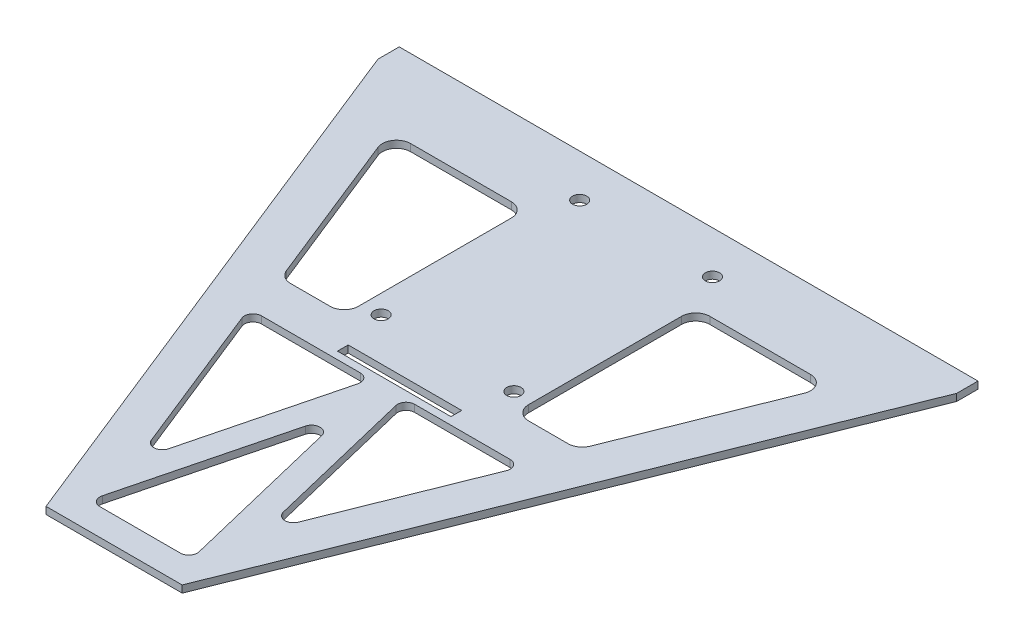
SolidWorks part; units mm, degrees
material "Teak"
ref_plane "Front Plane" through (0, 0, 0) normal (0, 0, 1) x (1, 0, 0)
ref_plane "Top Plane" through (0, 0, 0) normal (0, 1, 0) x (1, 0, 0)
ref_plane "Right Plane" through (0, 0, 0) normal (1, 0, 0) x (0, 0, -1)
sketch "Sketch2" plane through (0, 0, 0) normal (0, 1, 0) x (1, 0, 0)
  line L0 (0, 0) -> (259.08, 0)
  line L1 (259.08, 0) -> (160.02, -247.65)
  line L2 (160.02, -247.65) -> (99.06, -247.65)
  line L3 (99.06, -247.65) -> (0, 0)
  line L4 (0, 0) -> (0, -247.65) construction
  line L5 (0, -247.65) -> (400.3627, -247.65) construction
  line L6 (152.0793, -235.7108) -> (106.3593, -235.7108)
  line L7 (106.3593, -235.7108) -> (129.7724, -143.639)
  line L8 (129.7724, -143.639) -> (152.0793, -235.7108)
  line L9 (101.2964, -209.2418) -> (122.5734, -125.57)
  line L10 (122.5734, -125.57) -> (67.8277, -125.57)
  line L11 (67.8277, -125.57) -> (101.2964, -209.2418)
  line L12 (157.2265, -208.4139) -> (190.3641, -125.57)
  line L13 (190.3641, -125.57) -> (137.1554, -125.57)
  line L14 (137.1554, -125.57) -> (157.2265, -208.4139)
  dimension "D1" = 259.08
  dimension "D2" = 60.96
  dimension "D3" = 247.65
  dimension "D6" = 45.72
  dimension "D7" = 11.43
  dimension "D8" = 11.43
extrude "Boss-Extrude1" add sketch "Sketch2" along normal blind 3.175
fillet "Fillet1" radius 3.81 9 edges at (106.3593, 1.5875, 235.7108) (101.2964, 1.5875, 209.2418) (157.2265, 1.5875, 208.4139) (152.0793, 1.5875, 235.7108) (129.7724, 1.5875, 143.639) (122.5734, 1.5875, 125.57) (67.8277, 1.5875, 125.57) (137.1554, 1.5875, 125.57) (190.3641, 1.5875, 125.57)
sketch "Sketch3" plane through (0, 3.175, 0) normal (0, 1, 0) x (1, 0, 0)
  line L0 (129.54, 0) -> (129.54, -306.5161) construction
  line L1 (259.08, 0) -> (0, 0) construction
  line L2 (167.64, -25.4) -> (228.4025, -25.4)
  line L3 (228.4025, -25.4) -> (195.9545, -106.52)
  line L4 (195.9545, -106.52) -> (167.64, -106.52)
  line L5 (167.64, -106.52) -> (167.64, -25.4)
  line L6 (160.02, -247.65) -> (259.08, 0) construction
  line L7 (184.7366, -125.57) -> (141.9987, -125.57) construction
  line L8 (91.44, -106.52) -> (91.44, -25.4)
  line L9 (63.1255, -106.52) -> (91.44, -106.52)
  line L10 (30.6775, -25.4) -> (63.1255, -106.52)
  line L11 (91.44, -25.4) -> (30.6775, -25.4)
  dimension "D1" = 25.4
  dimension "D2" = 19.05
  dimension "D3" = 19.05
  dimension "D4" = 38.1
extrude "Cut-Extrude1" cut sketch "Sketch3" against normal up to surface (3.175 mm away) up to face at (129.54, 0, 123.825)
fillet "Fillet2" radius 6.35 8 edges at (167.64, 1.5875, 106.52) (195.9545, 1.5875, 106.52) (91.44, 1.5875, 106.52) (63.1255, 1.5875, 106.52) (91.44, 1.5875, 25.4) (30.6775, 1.5875, 25.4) (167.64, 1.5875, 25.4) (228.4025, 1.5875, 25.4)
sketch "Sketch4" plane through (0, 3.175, 0) normal (0, 1, 0) x (1, 0, 0)
  line L0 (0, 0) -> (0, 3.175)
  line L1 (0, 3.175) -> (259.0522, 3.175)
  line L2 (259.0522, 3.175) -> (259.08, 0)
  line L3 (259.08, 0) -> (0, 0)
  dimension "D1" = 3.175
sketch "Sketch5" plane through (0, 0, 0) normal (0, 0, -1) x (-1, 0, 0)
  line L4 (-259.08, 0) -> (0, 0)
  line L5 (0, 0) -> (0, 3.175)
  line L6 (0, 3.175) -> (-259.08, 3.175)
  line L7 (-259.08, 3.175) -> (-259.08, 0)
  line L8 (-259.08, 0) -> (0, 0)
  line L9 (0, 0) -> (0, 3.175)
  line L10 (0, 3.175) -> (-259.08, 3.175)
  line L11 (-259.08, 3.175) -> (-259.08, 0)
  dimension "D1" = 0
extrude "Boss-Extrude2" add sketch "Sketch5" along normal blind 4.7625
sketch "Sketch6" plane through (0, 3.175, 0) normal (0, 1, 0) x (1, 0, 0)
  line L0 (0, 3.175) -> (259.0522, 3.175) construction
  line L1 (104.1261, -117.4496) -> (154.9261, -117.4496)
  line L2 (104.1261, -117.4496) -> (104.1261, -122.2375)
  line L3 (104.1261, -122.2375) -> (154.9261, -122.2375)
  line L4 (154.9261, -117.4496) -> (154.9261, -122.2375)
  line L5 (0, 4.7625) -> (259.08, 4.7625) construction
  point P6 (129.5261, 3.175)
  point P7 (129.5261, -117.4496)
  dimension "D1" = 50.8
  dimension "D2" = 4.7879
  dimension "D3" = 127
extrude "Cut-Extrude2" cut sketch "Sketch6" against normal up to next
sketch "Sketch9" plane through (0, 0, -4.7625) normal (0, 0, -1) x (-1, 0, 0)
  line L0 (-259.08, 3.175) -> (-259.08, 0)
  line L1 (-259.08, 0) -> (0, 0)
  line L2 (0, 0) -> (0, 3.175)
  line L3 (0, 3.175) -> (-259.08, 3.175)
extrude "Boss-Extrude3" add sketch "Sketch9" along normal blind 4.7625
sketch "Sketch10" plane through (0, 3.175, 0) normal (0, 1, 0) x (1, 0, 0)
  line L0 (154.9261, -117.4496) -> (104.1261, -117.4496) construction
  line L1 (91.44, -100.17) -> (91.44, -31.75) construction
  line L3 (0, 9.525) -> (259.08, 9.525) construction
  circle A0 centre (99.822, -98.3996) radius 3.175
  circle A1 centre (159.258, -98.3996) radius 3.175
  circle A2 centre (99.822, -9.525) radius 3.175
  circle A3 centre (159.258, -9.525) radius 3.175
  point P12 (0, 0)
  point P13 (0, 0)
  dimension "D1" = 6.35
  dimension "D7" = 19.05
  dimension "D2" = 59.436
  dimension "D3" = 59.436
  dimension "D4" = 19.05
  dimension "D5" = 8.382
  dimension "D6" = 8.382
extrude "Cut-Extrude4" cut sketch "Sketch10" against normal through all
